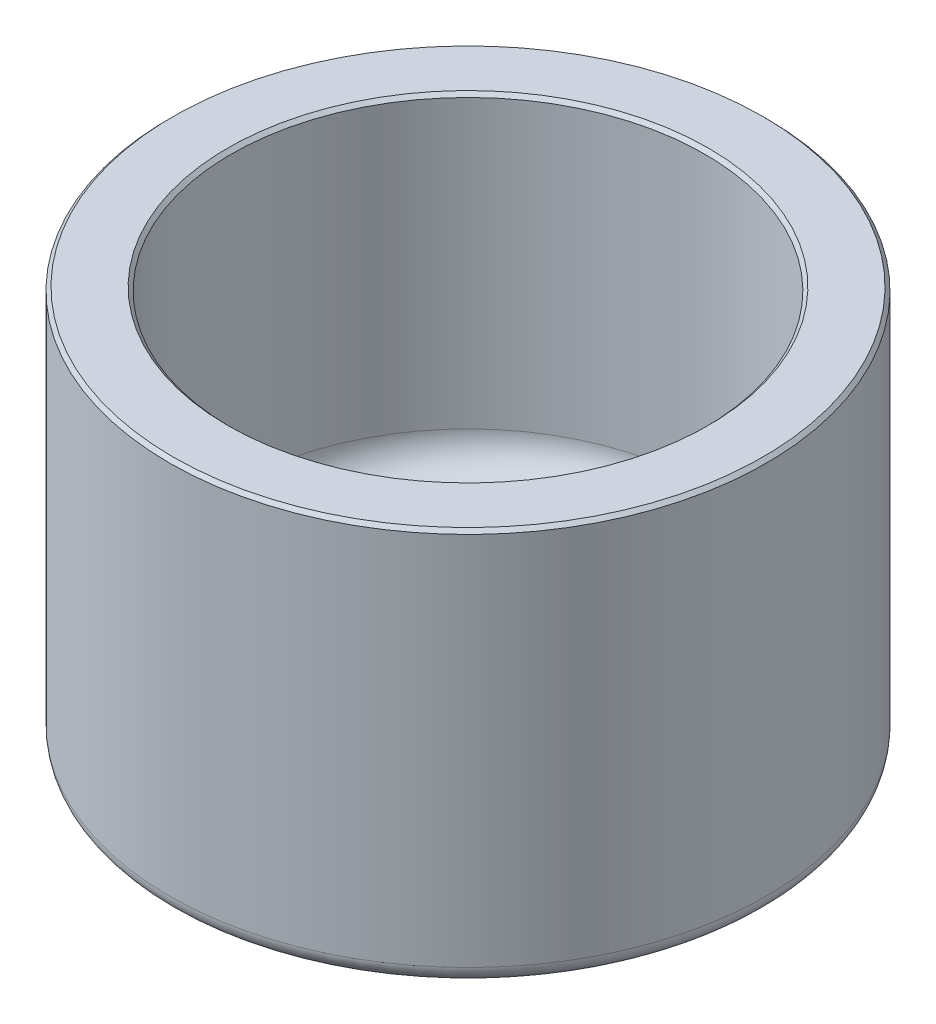
SolidWorks part; units mm, degrees
ref_plane "Front Plane" through (0, 0, 0) normal (0, 0, 1) x (1, 0, 0)
ref_plane "Top Plane" through (0, 0, 0) normal (0, 1, 0) x (1, 0, 0)
ref_plane "Right Plane" through (0, 0, 0) normal (1, 0, 0) x (0, 0, -1)
sketch "Sketch1" plane through (0, 0, 0) normal (0, 0, 1) x (1, 0, 0)
  line L0 (0, 0) -> (-16.95, 0)
  line L1 (-16.95, 0) -> (-16.95, 22.5)
  line L2 (-16.95, 22.5) -> (-13.45, 22.5)
  line L3 (-13.45, 22.5) -> (-13.45, 4)
  line L4 (-13.45, 4) -> (0, 4)
  line L5 (0, 4) -> (0, 0)
  dimension "D1" = 16.95
  dimension "D2" = 22.5
  dimension "D3" = 3.5
  dimension "D4" = 18.5
revolve "Revolve1" add sketch "Sketch1" angle 360 about L5
fillet "Fillet1" radius 1 1 edges at (0, 0, 16.95)
fillet "Fillet2" radius 2 1 edges at (0, 4, 13.45)
chamfer "Chamfer1" distance 0.2 angle 45 2 edges at (0, 22.5, 13.45) (0, 22.5, 16.95)
